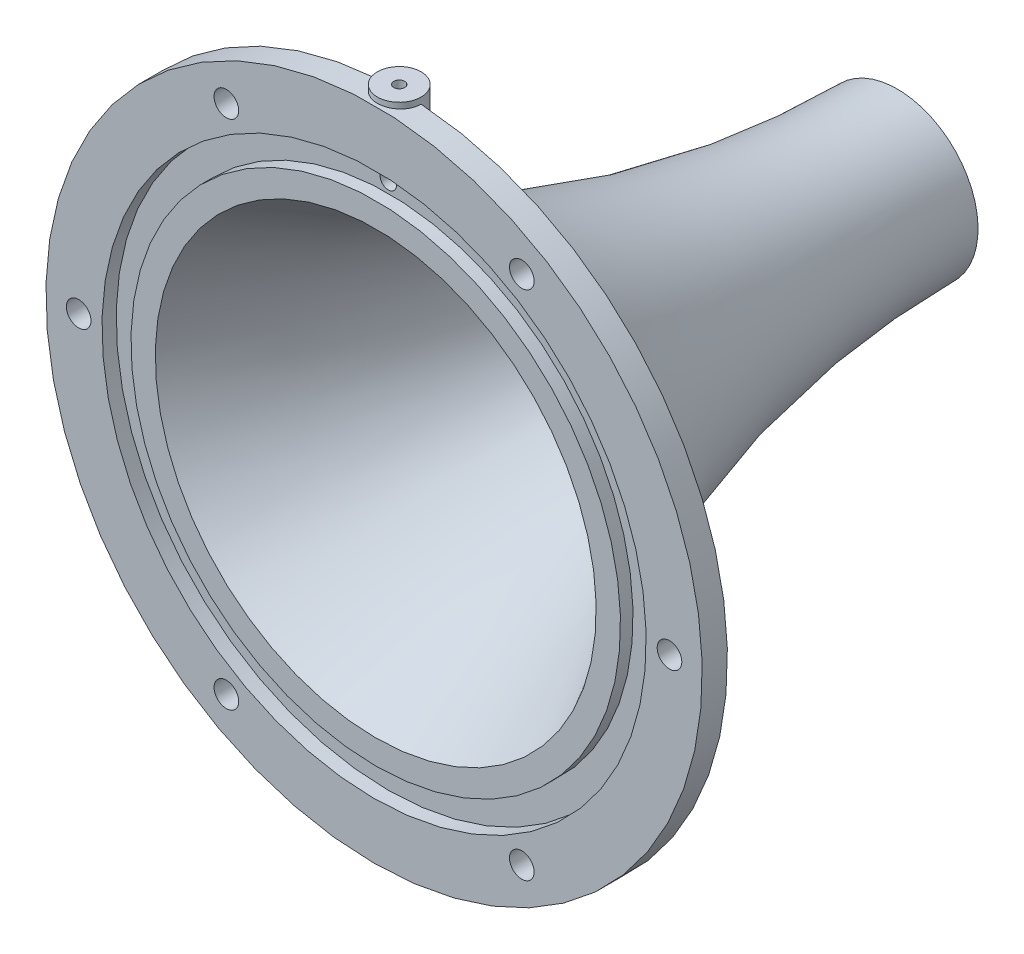
SolidWorks part; units mm, degrees
ref_plane "Front Plane" through (0, 0, 0) normal (0, 0, 1) x (1, 0, 0)
ref_plane "Top Plane" through (0, 0, 0) normal (0, 1, 0) x (1, 0, 0)
ref_plane "Right Plane" through (0, 0, 0) normal (1, 0, 0) x (0, 0, -1)
sketch "Sketch2" plane through (0, 0, 0) normal (1, 0, 0) x (0, 0, -1)
  line L0 (95.3, 14.75) -> (95.3, -11.2231) construction
  line L1 (-95.3, 0) -> (95.3, 0) construction
  line L2 (95.3, 14.75) -> (95.3, 12.75)
  line L18 (4.25, 40.3014) -> (4.25, 60)
  line L19 (4.25, 60) -> (-0.35, 60)
  line L20 (-0.35, 60) -> (-0.35, 49.75)
  line L21 (-0.35, 49.75) -> (2.25, 49.75)
  line L22 (2.25, 49.75) -> (2.25, 44.75)
  line L24 (-0.05, 44.75) -> (-0.05, 40.3014)
  line L25 (-0.05, 44.75) -> (2.25, 44.75)
  arc A0 (95.3, 14.75) -> (4.25, 40.3014) centre (95.3, 189.75) cw
  arc A3 (95.3, 12.75) -> (-0.05, 40.3014) centre (94.2097, 187.7466) cw
  point P0 (0, 0)
  dimension "D2" = 14.75
  dimension "D3" = 175
  dimension "D5" = 60
  dimension "D10" = 2.3
  dimension "D1" = 95.3
  dimension "D4" = 12.75
  dimension "D6" = 2.6
  dimension "D7" = 4.3
  dimension "D8" = 44.75
  dimension "D9" = 49.75
  dimension "D11" = 40.3014
revolve "Revolve1" add sketch "Sketch2" angle 360 about L1
ref_plane "Plane1" through (0, 61, 0) normal (0, -1, 0) x (-1, 0, 0)
sketch "Sketch3" plane through (0, 61, 0) normal (0, -1, 0) x (-1, 0, 0)
  line L0 (0, 7.8705) -> (0, -7.2207) construction
  line L1 (60, 4.25) -> (-60, 4.25) construction
  circle A1 centre (0, 4.25) radius 4
  dimension "D1" = 8
extrude "Boss-Extrude1" add sketch "Sketch3" along normal up to next
sketch "Sketch4" plane through (0, 61, 0) normal (0, 1, 0) x (1, 0, 0)
  circle A0 centre (0, 4.25) radius 1
  dimension "D1" = 2
extrude "Cut-Extrude1" cut sketch "Sketch4" against normal blind 14
sketch "Sketch5" plane through (0, 0, 0) normal (0, 0, 1) x (1, 0, 0)
  circle A0 centre (0, 46.7974) radius 1.5
  dimension "D1" = 3
extrude "Cut-Extrude2" cut sketch "Sketch5" against normal blind 5.2
sketch "Sketch6" plane through (0, 0, 0) normal (0, 0, 1) x (1, 0, 0)
  line L0 (0, 81.7811) -> (0, -82.905) construction
  line L1 (-27, -46.7654) -> (27, -46.7654) construction
  line L2 (125.0189, 0) -> (-91.9372, 0) construction
  circle A1 centre (54, 0) radius 2.25
  circle A11 centre (27, -46.7654) radius 2.25
  circle A12 centre (-27, -46.7654) radius 2.25
  circle A13 centre (-54, 0) radius 2.25
  circle A14 centre (-27, 46.7654) radius 2.25
  circle A15 centre (27, 46.7654) radius 2.25
  point P20 (0, 0)
  point P22 (0, 0)
  dimension "D1" = 54
  dimension "D2" = 4.5
  dimension "D4" = 54
  dimension "D3" = 6
extrude "Cut-Extrude3" cut sketch "Sketch6" against normal through all both and the other way through all
